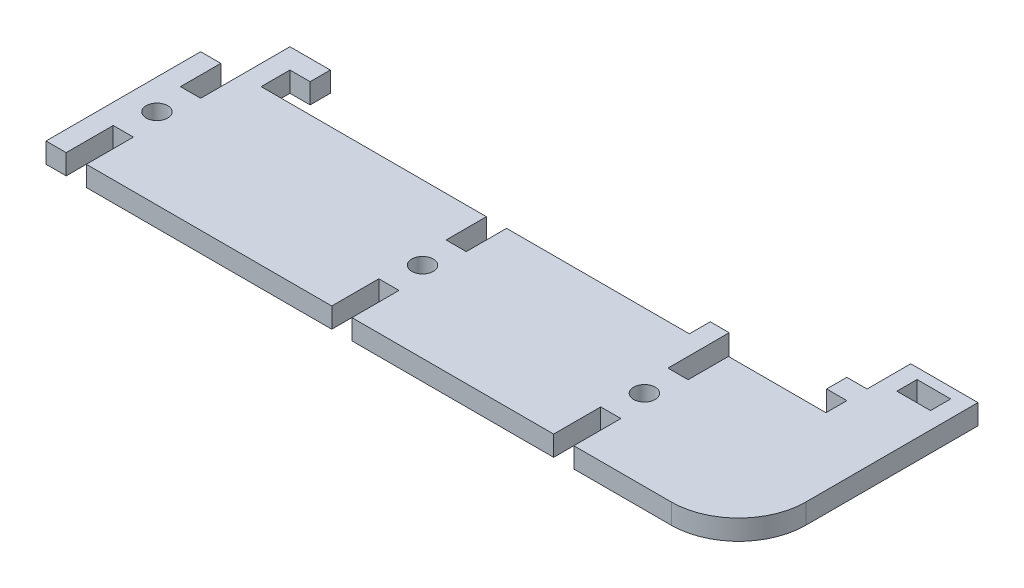
SolidWorks part; units mm, degrees
ref_plane "前视基准面" through (0, 0, 0) normal (0, 0, 1) x (1, 0, 0)
ref_plane "上视基准面" through (0, 0, 0) normal (0, 1, 0) x (1, 0, 0)
ref_plane "右视基准面" through (0, 0, 0) normal (1, 0, 0) x (0, 0, -1)
other "Configuration Table"
sketch "草图1" plane through (0, 0, 0) normal (0, 1, 0) x (1, 0, 0)
  line L0 (-64.6204, -23) -> (-64.6204, 0)
  line L1 (-64.6204, 0) -> (-61.6204, 0)
  line L2 (-61.6204, 0) -> (-61.6204, -6)
  line L3 (-61.6204, -6) -> (-58.6204, -6)
  line L4 (-58.6204, -6) -> (-58.6204, 7.2796)
  line L5 (-58.6204, 7.2796) -> (-52.6204, 7.2796)
  line L6 (-52.6204, 7.2796) -> (-52.6204, 4.2796)
  line L7 (-52.6204, 4.2796) -> (-55.6204, 4.2796)
  line L8 (-55.6204, 4.2796) -> (-55.6204, 0)
  line L9 (-55.6204, 0) -> (-22.1204, 0)
  line L10 (-22.1204, 0) -> (-22.1204, -6)
  line L11 (-22.1204, -6) -> (-19.1204, -6)
  line L12 (-19.1204, -6) -> (-19.1204, 0)
  line L13 (-19.1204, 0) -> (8.0584, 0)
  line L14 (8.0584, 0) -> (8.0584, 3.1124)
  line L15 (8.0584, 3.1124) -> (10.8796, 3.1124)
  line L16 (10.8796, 3.1124) -> (10.8796, -6)
  line L17 (10.8796, -6) -> (13.8796, -6)
  line L18 (13.8796, -6) -> (13.8796, 0)
  line L19 (13.8796, 0) -> (28.3796, 0)
  line L20 (28.3796, 0) -> (28.3796, 3.1124)
  line L21 (28.3796, 3.1124) -> (25.3704, 3.1124)
  line L22 (25.3704, 3.1124) -> (25.3704, 6.1124)
  line L23 (25.3704, 6.1124) -> (28.3796, 6.1124)
  line L24 (28.3796, 6.1124) -> (28.3796, 12.6124)
  line L25 (28.3796, 12.6124) -> (38.3796, 12.6124)
  line L26 (13.8796, -23) -> (28.3796, -23)
  line L27 (-64.6204, -23) -> (-61.6204, -23)
  line L28 (-61.6204, -23) -> (-61.6204, -16)
  line L29 (-61.6204, -16) -> (-58.6204, -16)
  line L30 (-58.6204, -16) -> (-58.6204, -23)
  line L31 (-58.6204, -23) -> (-22.1204, -23)
  line L32 (-22.1204, -23) -> (-22.1204, -16)
  line L33 (-22.1204, -16) -> (-19.1204, -16)
  line L34 (-19.1204, -16) -> (-19.1204, -23)
  line L35 (-19.1204, -23) -> (10.8796, -23)
  line L36 (10.8796, -23) -> (10.8796, -16)
  line L37 (10.8796, -16) -> (13.8796, -16)
  line L38 (13.8796, -16) -> (13.8796, -23)
  line L39 (38.3796, -13) -> (38.3796, 12.6124)
  line L40 (35.8796, 11.0486) -> (35.8796, 8.0486)
  line L45 (30.8796, 11.0486) -> (35.8796, 11.0486)
  line L47 (35.8796, 8.0486) -> (30.8796, 8.0486)
  line L49 (30.8796, 8.0486) -> (30.8796, 11.0486)
  arc A0 (28.3796, -23) -> (38.3796, -13) centre (28.3796, -13) ccw
  circle A1 centre (-60.1204, -11) radius 1.6
  circle A2 centre (-20.6204, -11) radius 1.6
  circle A3 centre (12.3796, -11) radius 1.6
  dimension "D21" = 10
  dimension "D1" = 23
  dimension "D2" = 3
  dimension "D3" = 3
  dimension "D4" = 3
  dimension "D5" = 3
  dimension "D6" = 6
  dimension "D7" = 3
  dimension "D8" = 3
  dimension "D9" = 36.5
  dimension "D10" = 30
  dimension "D11" = 3
  dimension "D12" = 6
  dimension "D13" = 3
  dimension "D14" = 14.5
  dimension "D15" = 6.5
  dimension "D16" = 14.5
  dimension "D17" = 7
  dimension "D18" = 6
  dimension "D19" = 3
  dimension "D20" = 10
  dimension "D22" = 3
  dimension "D23" = 5
extrude "凸台-拉伸3" add sketch "草图1" against normal blind 3 contours L26 A0 L39 L25 L24 L23 L22 L21 L20 L19 L18 L17 L16 L15 L14 L13 L12 L11 L10 L9 L8 L7 L6 L5 L4 L3 L2 L1 L0 L27 L28 L29 L30 L31 L32 L33 L34 L35 L36 L37 L38 A3 A2 A1 L47 L49 L45
